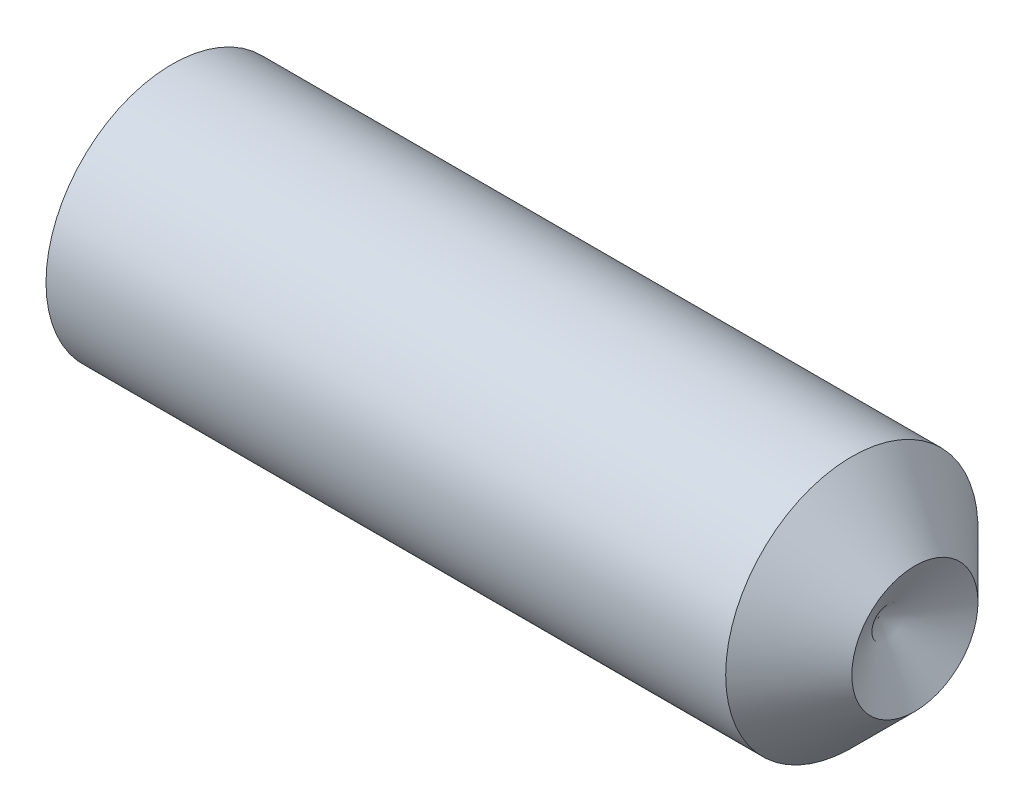
SolidWorks part; units mm, degrees
revolve "BaseBody" add sketch "BodySke" angle 360 about L5
sketch "BodySke" plane through (0, 0, 0) normal (0, 0, 1) x (1, 0, 0)
  line L0 (0, 0) -> (0, 1.61)
  line L1 (0, 1.61) -> (0.2252, 2)
  line L2 (0.2252, 2) -> (11, 2)
  line L3 (11, 2) -> (12, 1)
  line L4 (11.4226, 0) -> (0, 0)
  line L5 (-12.7, 0) -> (88.9, 0) construction
  line L6 (11.4226, 0) -> (12, 1)
  line L7 (12, 1) -> (12, 10.525) construction
  line L8 (0, -1.61) -> (0.2252, -2) construction
  line L9 (11.4226, 0) -> (12, -1) construction
  line L10 (11, -2) -> (12, -1) construction
  line L11 (0.35, 15.875) -> (0.35, -3.175) construction
  dimension "Diameter" = 4
  dimension "Drive_ch_ang" = 60
  dimension "Minor_dia" = 3.22
  dimension "Cup_ang" = 120
  dimension "Cup_dia" = 2
  dimension "Length" = 12
  dimension "Cup_nose_ang" = 45
  dimension "Advance" = 0.7
cosmetic thread "ThreadCosmetic" [suppressed] parameters "Thread_minor"=3.22
material "Plain Carbon Steel"
ref_plane "Plane1" through (0, 0, 0) normal (0, 0, 1) x (1, 0, 0)
ref_plane "Plane2" through (0, 0, 0) normal (0, 1, 0) x (1, 0, 0)
ref_plane "Plane3" through (0, 0, 0) normal (1, 0, 0) x (0, 0, -1)
sketch "Sketch2" plane through (0, 0, 0) normal (-1, 0, 0) x (0, 0, 1)
  line L0 (0.5774, 1) -> (-0.5774, 1)
  line L1 (-0.5774, 1) -> (-1.1547, 0)
  line L2 (0.5774, 1) -> (1.1547, 0)
  line L3 (0.5774, -1) -> (1.1547, 0)
  line L4 (0.5774, -1) -> (-0.5774, -1)
  line L5 (-0.5774, -1) -> (-1.1547, 0)
  dimension "Hex_size" = 2
  dimension "D2" = 1
  dimension "D3" = 1
extrude "Hex" cut sketch "Sketch2" against normal blind 2.5
sketch "ThdSchSke" plane through (0, 0, 0) normal (0, 0, 1) x (1, 0, 0)
  line L0 (0.2252, -1.61) -> (-0.0479, -2)
  line L1 (0.2252, -1.61) -> (0.4982, -2)
  line L2 (0.4982, -2) -> (0.4982, -2.5)
  line L3 (-3.175, 0) -> (5.1513, 0) construction
  line L4 (0.2252, 2) -> (0.2252, -2) construction
  line L5 (0.4982, -2.5) -> (-0.0479, -2.5)
  line L6 (-0.0479, -2.5) -> (-0.0479, -2)
  dimension "Thread_minor" = 3.22
  dimension "Diameter" = 4
revolve "ThreadSchematic" [suppressed] cut sketch "ThdSchSke" angle 360 about L3
pattern_linear "ThdSchPat" [suppressed]
equation "\"D2@Sketch2\" = \"Hex_size@Sketch2\" / 2"
equation "\"D3@Sketch2\" = \"Hex_size@Sketch2\" / 2"
equation "\"Thread_minor@ThreadCosmetic\" = \"Minor_dia@BodySke\""
equation "\"Thread_minor@ThdSchSke\" = \"Thread_minor@ThreadCosmetic\""
equation "\"Diameter@ThdSchSke\" = \"Diameter@BodySke\""
equation "\"Overcut@ThdSchSke\" = \"Diameter@BodySke\" * 1.25"
equation "\"Num_threads@ThdSchPat\" = int( (\"Length@BodySke\" - ( ( ( \"Diameter@BodySke\" - \"Minor_dia@BodySke\" ) * 0.5 ) / tan( \"Drive_ch_ang@BodySke\" * 0.017453292 ) ) - ( ( ( \"Diameter@BodySke\" - \"Cup_dia@BodySke\" ) * 0.5 ) * tan( \"Cup_nose_ang@BodySke\" * 0.017453292 ) ) ) / \"Advance@BodySke\" + 0.999 )  + 1"
equation "\"Advance@ThdSchPat\" = (\"Length@BodySke\" - ( ( ( \"Diameter@BodySke\" - \"Minor_dia@BodySke\" ) * 0.5 ) / tan( \"Drive_ch_ang@BodySke\" * 0.017453292 ) ) - ( ( ( \"Diameter@BodySke\" - \"Cup_dia@BodySke\" ) * 0.5 ) * tan( \"Cup_nose_ang@BodySke\" * 0.017453292 ) ) ) /  (\"Num_threads@ThdSchPat\" - 1) 'relax it"
equation "' \"Num_threads@ThdSchPat\" = \"Num_threads@ThdSchPat\" - sgn( \"Num_threads@ThdSchPat\" - 1) '---chamfered tips only---"
